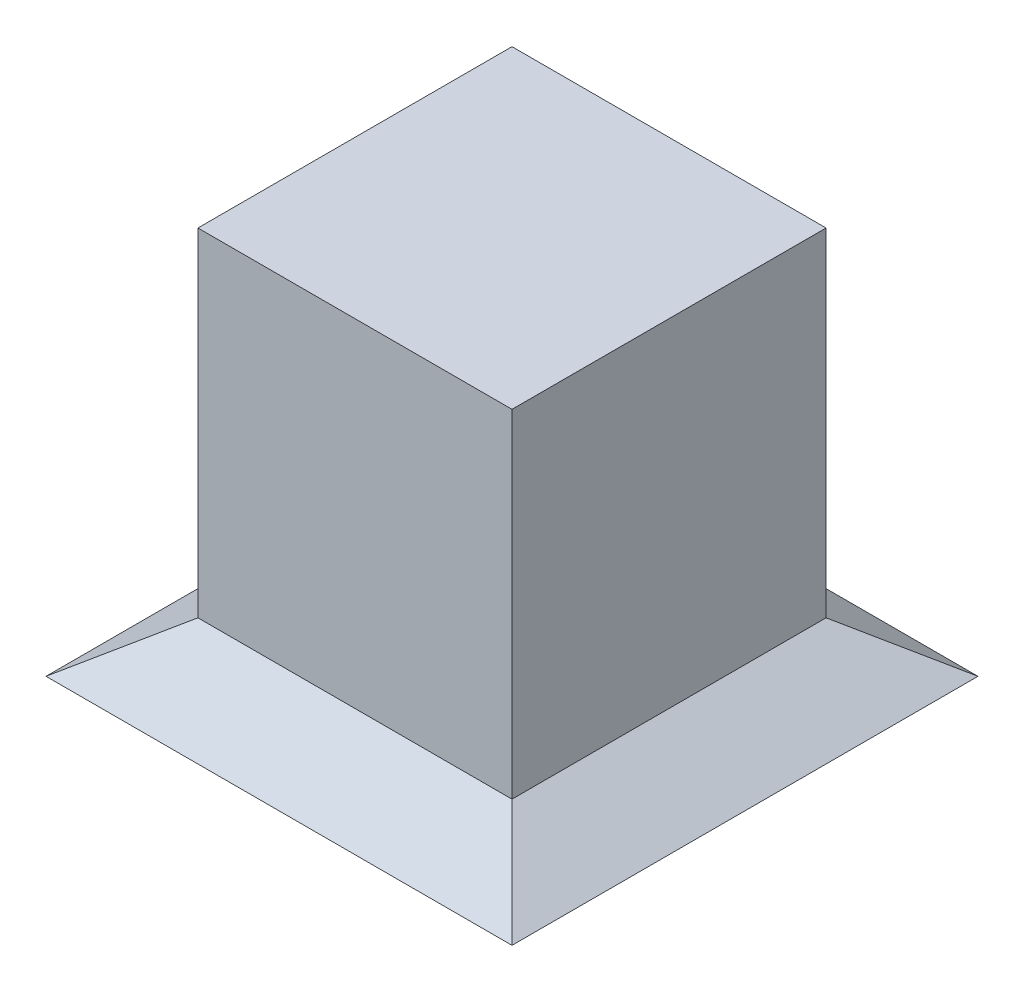
SolidWorks part; units mm, degrees
ref_plane "Front Plane" through (0, 0, 0) normal (0, 0, 1) x (1, 0, 0)
ref_plane "Top Plane" through (0, 0, 0) normal (0, 1, 0) x (1, 0, 0)
ref_plane "Right Plane" through (0, 0, 0) normal (1, 0, 0) x (0, 0, -1)
sketch "Sketch1" plane through (0, 0, 0) normal (0, 1, 0) x (1, 0, 0)
  line L7 (-24, 24) -> (24, 24)
  line L8 (-24, 24) -> (-24, -24)
  line L9 (-24, -24) -> (24, -24)
  line L10 (24, 24) -> (24, -24)
  point P0 (0, 0)
  point P1 (0, 0)
  point P2 (0, 0)
  point P3 (0, 0)
  point P4 (0, 0)
  point P6 (0, 0)
  point P11 (0, 0)
  dimension "D1" = 24
  dimension "D2" = 24
  dimension "D3" = 48
  dimension "D4" = 48
  dimension "D5" = 24
  dimension "D6" = 24
ref_plane "Plane1" through (0, 4, 0) normal (0, 1, 0) x (1, 0, 0)
ref_plane "Plane2" through (0, 2, 0) normal (0, 1, 0) x (1, 0, 0)
sketch "Sketch2" plane through (0, 4, 0) normal (0, 1, 0) x (1, 0, 0)
  line L1 (-18, 18) -> (18, 18)
  line L2 (-18, 18) -> (-18, -18)
  line L3 (-18, -18) -> (18, -18)
  line L4 (18, 18) -> (18, -18)
  point P0 (0, 0)
  dimension "D1" = 36
  dimension "D2" = 36
  dimension "D3" = 18
  dimension "D4" = 18
loft "Loft1" add profiles "Sketch1", "Sketch2"
shell "Shell4" thickness 2
sketch "Sketch8" plane through (0, 6, 0) normal (0, 1, 0) x (1, 0, 0)
  line L1 (-18.6056, 18.6056) -> (18.6056, 18.6056)
  line L2 (-18.6056, 18.6056) -> (-18.6056, -18.6056)
  line L3 (-18.6056, -18.6056) -> (18.6056, -18.6056)
  line L4 (18.6056, 18.6056) -> (18.6056, -18.6056)
  line L5 (-18.6056, 18.6056) -> (18.6056, -18.6056) construction
  line L6 (-18.6056, -18.6056) -> (18.6056, 18.6056) construction
  point P0 (0, 0)
  point P7 (19.8121, -19.0106)
  point P8 (-32.7467, -2.3111)
  point P9 (8.182, 10.0645)
extrude "Boss-Extrude1" add sketch "Sketch8" along normal blind 40
